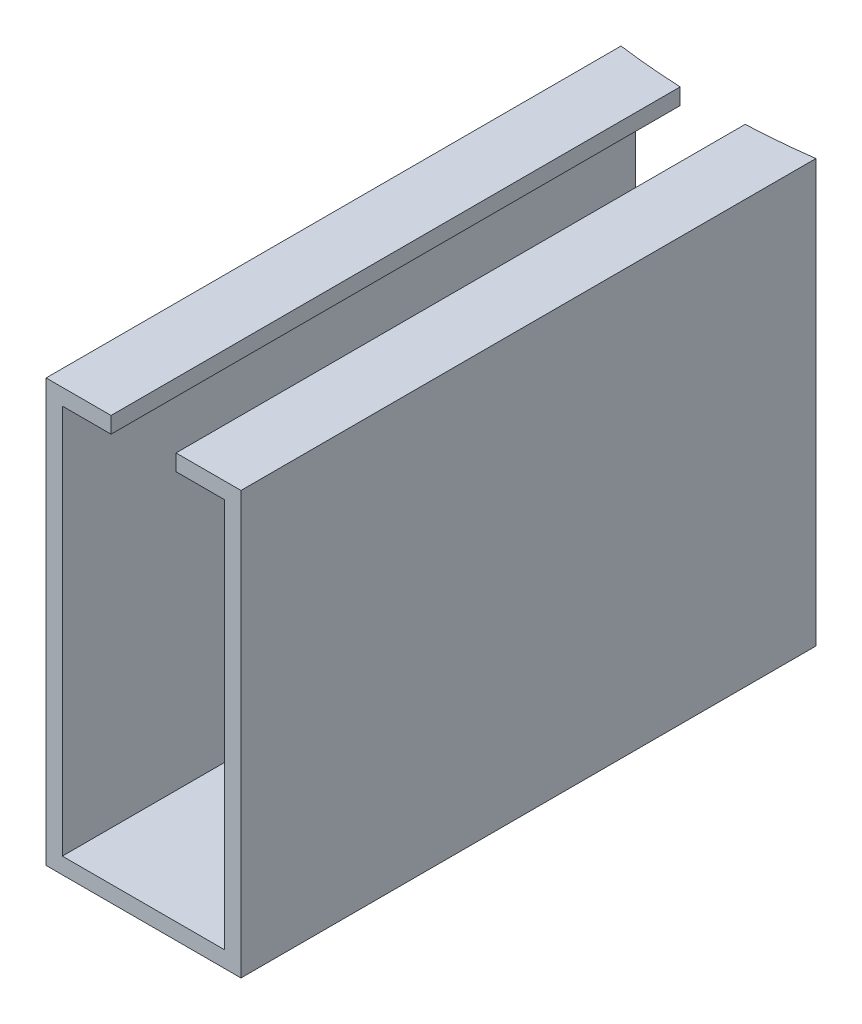
SolidWorks part; units mm, degrees
material "ABS"
ref_plane "正面" through (0, 0, 0) normal (0, 0, 1) x (1, 0, 0)
ref_plane "平面" through (0, 0, 0) normal (0, 1, 0) x (1, 0, 0)
ref_plane "右側面" through (0, 0, 0) normal (1, 0, 0) x (0, 0, -1)
sketch "ｽｹｯﾁ1" plane through (0, 0, 0) normal (0, 0, 1) x (1, 0, 0)
  line L0 (0, 0) -> (5, 0)
  line L1 (0, 0) -> (0, 12)
  line L3 (-0.5, 12) -> (-0.5, -0.5)
  line L4 (-0.5, -0.5) -> (5.5, -0.5)
  line L5 (5.5, -0.5) -> (5.5, 12)
  line L7 (5, 12) -> (5, 0)
  line L8 (-0.5, 12) -> (-0.5, 12.5)
  line L9 (-0.5, 12.5) -> (1.5, 12.5)
  line L10 (1.5, 12.5) -> (1.5, 12)
  line L11 (1.5, 12) -> (0, 12)
  line L12 (5.5, 12) -> (5.5, 12.5)
  line L13 (5.5, 12.5) -> (3.5, 12.5)
  line L14 (3.5, 12.5) -> (3.5, 12)
  line L15 (3.5, 12) -> (5, 12)
  dimension "D1" = 5
  dimension "D2" = 12
  dimension "D3" = 0.5
  dimension "D4" = 12.5
  dimension "D5" = 6
  dimension "D6" = 12.5
  dimension "D7" = 0.5
  dimension "D8" = 0.5
  dimension "D9" = 2
  dimension "D10" = 2
  dimension "D11" = 0.5
extrude "ﾎﾞｽ - 押し出し1" add sketch "ｽｹｯﾁ1" along normal blind 40
sketch "ｽｹｯﾁ2" plane through (0, -0.5, 0) normal (0, -1, 0) x (1, 0, 0)
  line L0 (2.5, 40) -> (2.5, 0)
  line L1 (-0.5, 40) -> (5.5, 40) construction
  line L2 (-0.5, 0) -> (5.5, 0) construction
  circle A0 centre (2.5, 0) radius 22.5
  dimension "D1" = 45
extrude "ｶｯﾄ - 押し出し1" cut sketch "ｽｹｯﾁ2" against normal blind 40 contours A0
